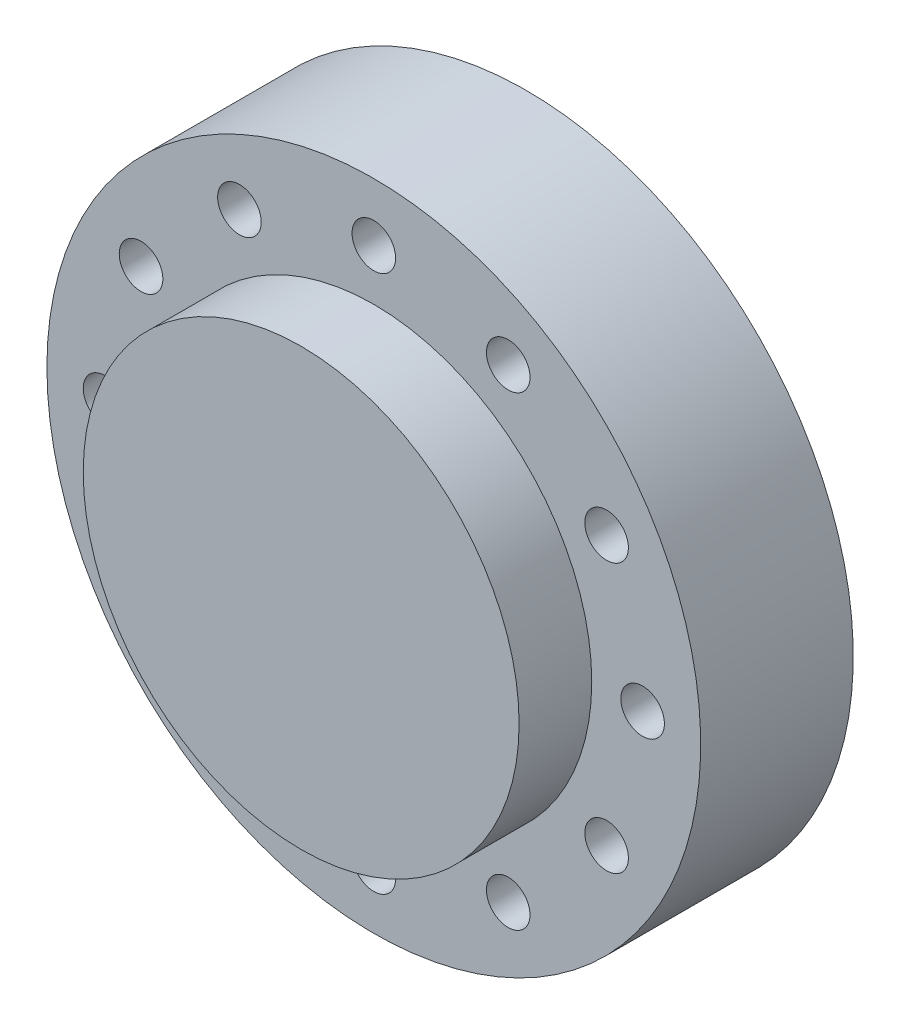
SolidWorks part; units mm, degrees
ref_plane "前视基准面" through (0, 0, 0) normal (0, 0, 1) x (1, 0, 0)
ref_plane "上视基准面" through (0, 0, 0) normal (0, 1, 0) x (1, 0, 0)
ref_plane "右视基准面" through (0, 0, 0) normal (1, 0, 0) x (0, 0, -1)
other "Configuration Table"
sketch "草图1" plane through (0, 0, 0) normal (0, 0, 1) x (1, 0, 0)
  circle A0 centre (0, 0) radius 22.5
  dimension "D1" = 45
extrude "凸台-拉伸1" add sketch "草图1" along normal blind 10.5
sketch "草图2" plane through (0, 0, 10.5) normal (0, 0, 1) x (1, 0, 0)
  circle A0 centre (0, 0) radius 15
  dimension "D1" = 30
extrude "凸台-拉伸2" add sketch "草图2" along normal blind 5
sketch "草图3" plane through (0, 0, 10.5) normal (0, 0, 1) x (1, 0, 0)
  circle A0 centre (0, 0) radius 18.5 construction
  circle A1 centre (0, 18.5) radius 1.5
  dimension "D1" = 37
  dimension "D2" = 3
extrude "切除-拉伸1" cut sketch "草图3" against normal blind 5
sketch "草图5" plane through (0, 0, 10.5) normal (0, 0, 1) x (1, 0, 0)
  circle A0 centre (0, 18.5) radius 1.5
  dimension "D1" = 3
extrude "切除-拉伸2" cut sketch "草图5" against normal through all
sketch "草图9" plane through (0, 0, 0) normal (0, 0, -1) x (-1, 0, 0)
  line L1 (1.314, 21.7052) -> (-2.1188, 21.2406)
  line L2 (-2.1188, 21.2406) -> (-3.4328, 18.0353)
  line L3 (-3.4328, 18.0353) -> (-1.314, 15.2948)
  line L4 (-1.314, 15.2948) -> (2.1188, 15.7594)
  line L5 (2.1188, 15.7594) -> (3.4328, 18.9647)
  line L6 (3.4328, 18.9647) -> (1.314, 21.7052)
  circle A0 centre (0, 18.5) radius 3 construction
  dimension "D1" = 6
extrude "切除-拉伸6" cut sketch "草图9" against normal blind 3
pattern_circular "阵列(圆周)1" count 12 over 360 about axis through (0, 0, 0) along (0, 0, 1) of "切除-拉伸1", "切除-拉伸6", "切除-拉伸2"
